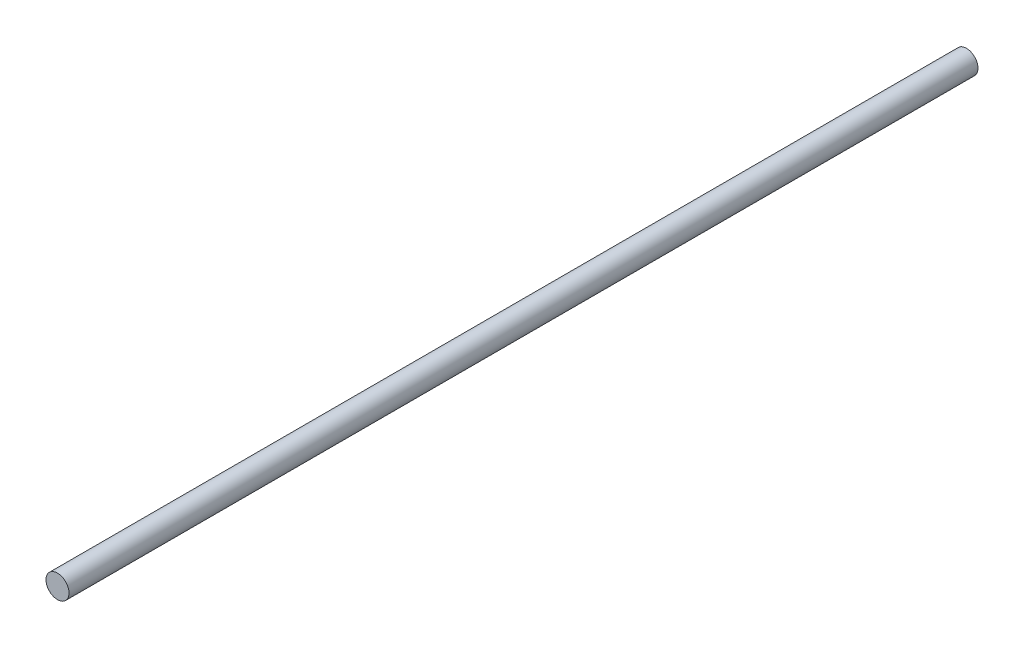
SolidWorks part; units mm, degrees
ref_plane "Alzado" through (0, 0, 0) normal (0, 0, 1) x (1, 0, 0)
ref_plane "Planta" through (0, 0, 0) normal (0, 1, 0) x (1, 0, 0)
ref_plane "Vista lateral" through (0, 0, 0) normal (1, 0, 0) x (0, 0, -1)
sketch "Croquis1" plane through (0, 0, 0) normal (0, 0, 1) x (1, 0, 0)
  circle A0 centre (0, 0) radius 4.5
  dimension "D1" = 9
extrude "Saliente-Extruir1" add sketch "Croquis1" along normal blind 355
